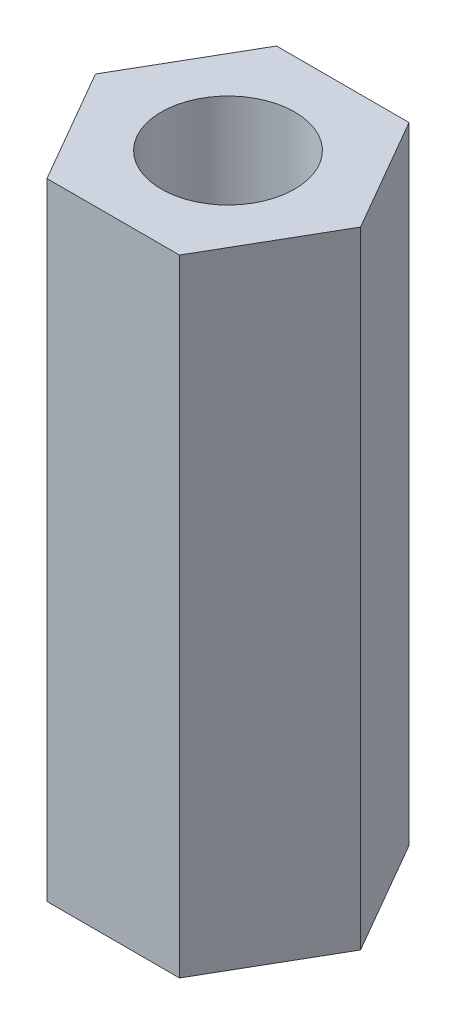
SolidWorks part; units mm, degrees
ref_plane "前视基准面" through (0, 0, 0) normal (0, 0, 1) x (1, 0, 0)
ref_plane "上视基准面" through (0, 0, 0) normal (0, 1, 0) x (1, 0, 0)
ref_plane "右视基准面" through (0, 0, 0) normal (1, 0, 0) x (0, 0, -1)
other "Configuration Table"
sketch "草图1" plane through (0, 0, 0) normal (0, 1, 0) x (1, 0, 0)
  line L1 (3.1754, 0) -> (1.5877, 2.75)
  line L2 (1.5877, 2.75) -> (-1.5877, 2.75)
  line L3 (-1.5877, 2.75) -> (-3.1754, 0)
  line L4 (-3.1754, 0) -> (-1.5877, -2.75)
  line L5 (-1.5877, -2.75) -> (1.5877, -2.75)
  line L6 (1.5877, -2.75) -> (3.1754, 0)
  circle A0 centre (0, 0) radius 2.75 construction
  dimension "D1" = 5.5
extrude "凸台-拉伸1" add sketch "草图1" along normal blind 15
sketch "草图2" plane through (0, 0, 0) normal (0, -1, 0) x (1, 0, 0)
  circle A0 centre (0, 0) radius 1.6
  dimension "D1" = 3.2
extrude "切除-拉伸1" cut sketch "草图2" against normal blind 15
